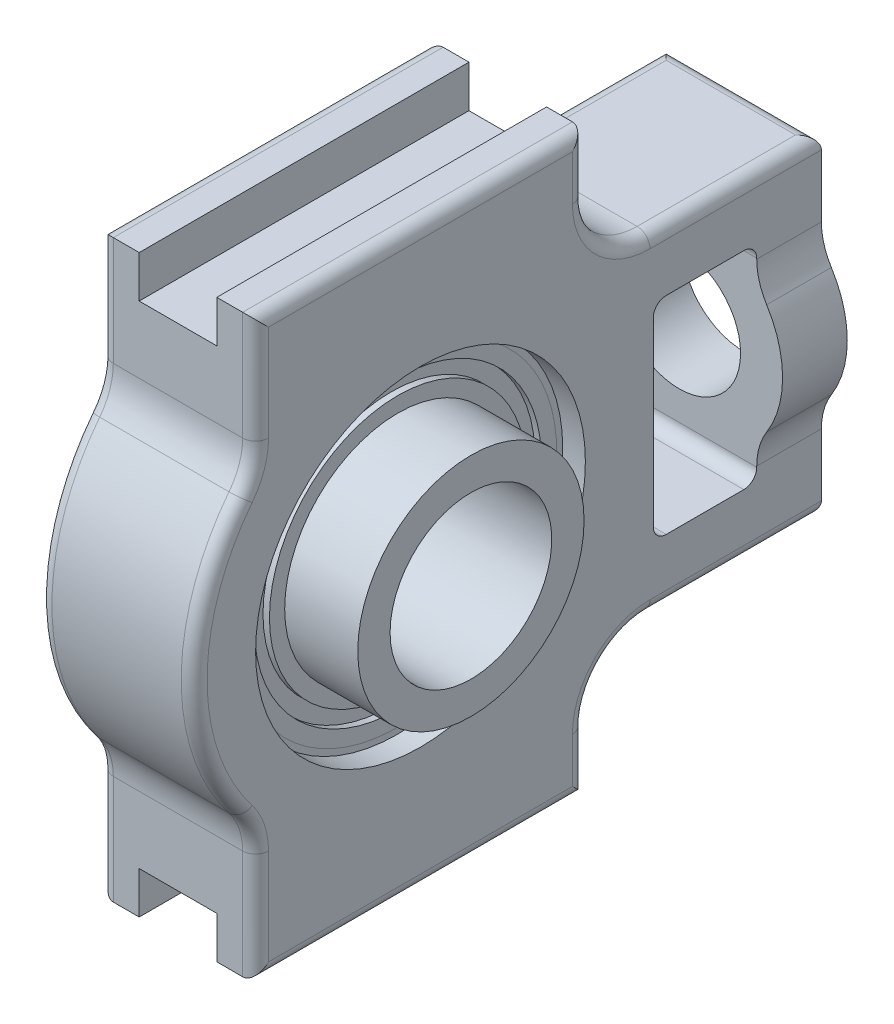
SolidWorks part; units mm, degrees
material "S45C"
ref_plane "Front Plane" through (0, 0, 0) normal (0, 0, 1) x (1, 0, 0)
ref_plane "Top Plane" through (0, 0, 0) normal (0, 1, 0) x (1, 0, 0)
ref_plane "Right Plane" through (0, 0, 0) normal (1, 0, 0) x (0, 0, -1)
sketch "Sketch1" plane through (0, 0, 0) normal (1, 0, 0) x (0, 0, -1)
  line L0 (25.5, 25.5) -> (25.5, 44.5)
  line L1 (-25.5, -44.5) -> (25.5, -44.5)
  line L2 (-25.5, -44.5) -> (-25.5, -23.9739)
  line L3 (-25.5, 44.5) -> (25.5, 44.5)
  line L4 (25.5, -44.5) -> (25.5, -25.5)
  line L5 (-25.5, -44.5) -> (25.5, 44.5) construction
  line L6 (-25.5, 44.5) -> (25.5, -44.5) construction
  line L7 (25.5, 25.5) -> (62, 25.5)
  line L8 (0, 0) -> (62, 0) construction
  line L9 (25.5, -25.5) -> (62, -25.5)
  line L10 (62, 25.5) -> (62, -25.5)
  line L11 (-25.5, 23.9739) -> (-25.5, 44.5)
  line L13 (36, -16) -> (52, -16)
  line L14 (36, -16) -> (36, 16)
  line L15 (36, 16) -> (52, 16)
  line L16 (52, -16) -> (52, 16)
  line L17 (36, -16) -> (52, 16) construction
  line L18 (36, 16) -> (52, -16) construction
  arc A0 (-25.5, 23.9739) -> (-25.5, -23.9739) centre (0, 0) ccw
  point P0 (0, 0)
  point P12 (44, 0)
  dimension "L3" = 51
  dimension "L" = 97
  dimension "H" = 89
  dimension "H2" = 51
  dimension "L1" = 62
  dimension "N2" = 32
  dimension "N1" = 16
  dimension "L2" = 10
extrude "Extrude1" add sketch "Sketch1" along normal mid plane 24
sketch "Sketch2" plane through (0, 0, -62) normal (0, 0, -1) x (-1, 0, 0)
  circle A0 centre (0, 0) radius 16
  dimension "A" = 32
extrude "Extrude2" add sketch "Sketch2" against normal up to vertex
sketch "Sketch3" plane through (0, 0, -62) normal (0, 0, -1) x (-1, 0, 0)
  circle A0 centre (0, 0) radius 9.5
  dimension "N" = 19
extrude "Extrude3" cut sketch "Sketch3" against normal up to next
sketch "Sketch4" plane through (0, 0, -25.5) normal (0, 0, -1) x (-1, 0, 0)
  line L0 (-12, 44.5) -> (12, 44.5) construction
  line L1 (-6, 38) -> (6, 38)
  line L2 (-6, 38) -> (-6, 44.5)
  line L3 (-6, 44.5) -> (6, 44.5)
  line L4 (6, 38) -> (6, 44.5)
  line L5 (-6, 38) -> (6, 44.5) construction
  line L6 (-6, 44.5) -> (6, 38) construction
  line L7 (-12, -44.5) -> (12, -44.5) construction
  line L8 (-6, -38) -> (6, -38)
  line L9 (-6, -38) -> (-6, -44.5)
  line L10 (-6, -44.5) -> (6, -44.5)
  line L11 (6, -38) -> (6, -44.5)
  line L12 (-6, -38) -> (6, -44.5) construction
  line L13 (-6, -44.5) -> (6, -38) construction
  line L14 (0, -41.25) -> (0, 41.25) construction
  point P0 (0, 41.25)
  point P7 (0, -41.25)
  dimension "A1" = 12
  dimension "H1" = 76
extrude "Extrude4" cut sketch "Sketch4" against normal through all
sketch "Sketch5" plane through (0, 0, 0) normal (0, 0, 1) x (1, 0, 0)
  line L0 (8.5, 25.5) -> (8.5, 24.5713)
  line L2 (12, 25.5) -> (12, 0)
  line L3 (12, 0) -> (-12, 0)
  line L4 (-12, 0) -> (-12, 25.5)
  line L6 (-8.5, 25.5) -> (-8.5, 24.5713)
  line L7 (0, 0) -> (0, 26) construction
  line L8 (19.8658, 0) -> (-20.2621, 0) construction
  line L9 (12, 25.5) -> (-12, 25.5) construction
  line L10 (12, 25.5) -> (8.5, 25.5)
  line L11 (-8.5, 25.5) -> (-12, 25.5)
  arc A0 (8.5, 24.5713) -> (-8.5, 24.5713) centre (0, 0) ccw
  dimension "D" = 52
  dimension "C" = 17
revolve "Cut-Revolve1" cut sketch "Sketch5" angle 360 about L8
fillet "Fillet1" radius 10 8 edges at (0, -23.9739, 25.5) (0, 23.9739, 25.5) (0, -25.5, -25.5) (0, 25.5, -25.5) (-12, -10.583, -57) (-12, 10.583, -57) (12, -10.583, -57) (12, 10.583, -57)
fillet "Fillet2" radius 2 32 edges at (-12, -25.5, -48.75) (-12, -40, -25.5) (12, -40, -25.5) (12, -25.5, -48.75) (-12, 40, -25.5) (-12, 25.5, -48.75) (12, 25.5, -48.75) (12, 40, -25.5) (12, 36.0771, 25.5) (12, 24.4052, 26.0425) (12, -36.0771, 25.5) (12, -24.4052, 26.0425) (-12, 36.0771, 25.5) (-12, 24.4052, 26.0425) (-12, -36.0771, 25.5) (-12, -24.4052, 26.0425) (-12, -28.4289, -28.4289) (12, -28.4289, -28.4289) (-12, 28.4289, -28.4289) (12, 28.4289, -28.4289) (12, 0, 35) (-12, 0, 35) (0, -25.5, -62) (0, 25.5, -62) (0, -16, -36) (0, -16, -52) (0, 16, -52) (0, 16, -36) (-12, -44.5, 0) (12, -44.5, 0) (-12, 44.5, 0) (12, 44.5, 0)
sketch "Sketch7" plane through (0, 0, 0) normal (0, 0, 1) x (1, 0, 0)
  line L0 (-8.5, 24.5713) -> (-8.5, 22.2142)
  line L1 (-8.5, 25.5) -> (-8.5, -25.5) construction
  line L2 (-8.5, 17.5) -> (-14.3, 17.5)
  line L3 (-14.3, 17.5) -> (-14.3, 12.5)
  line L4 (-14.3, 12.5) -> (19.8, 12.5)
  line L5 (19.8, 12.5) -> (19.8, 17.5)
  line L6 (19.8, 17.5) -> (8.5, 17.5)
  line L7 (8.5, -25.5) -> (8.5, 25.5) construction
  line L8 (8.5, 17.5) -> (8.5, 19.8571)
  line L9 (0, 0) -> (28.2877, 0) construction
  line L10 (-8.5, 19.8571) -> (-8.5, 17.5)
  line L11 (-8.5, 22.2142) -> (-7.5, 22.2142)
  line L12 (8.5, 22.2142) -> (8.5, 24.5713)
  line L13 (-8.5, 19.8571) -> (-7.5, 19.8571)
  line L14 (-7.5, 22.2142) -> (-7.5, 19.8571)
  line L15 (7.5, 19.8571) -> (8.5, 19.8571)
  line L16 (7.5, 19.8571) -> (7.5, 22.2142)
  line L17 (7.5, 22.2142) -> (8.5, 22.2142)
  arc A0 (8.5, 24.5713) -> (-8.5, 24.5713) centre (0, 0) ccw construction
  arc A1 (8.5, 24.5713) -> (-8.5, 24.5713) centre (0, 0) ccw
  dimension "D1" = 5
  dimension "DIAMETER SHAFT" = 25
  dimension "S" = 14.3
  dimension "B" = 34.1
  dimension "D4" = 1
revolve "Revolve1" add sketch "Sketch7" angle 360 about L9
equation "\"D1@Sketch7\" =  sqr( \"DIAMETER SHAFT@Sketch7\" ) "
